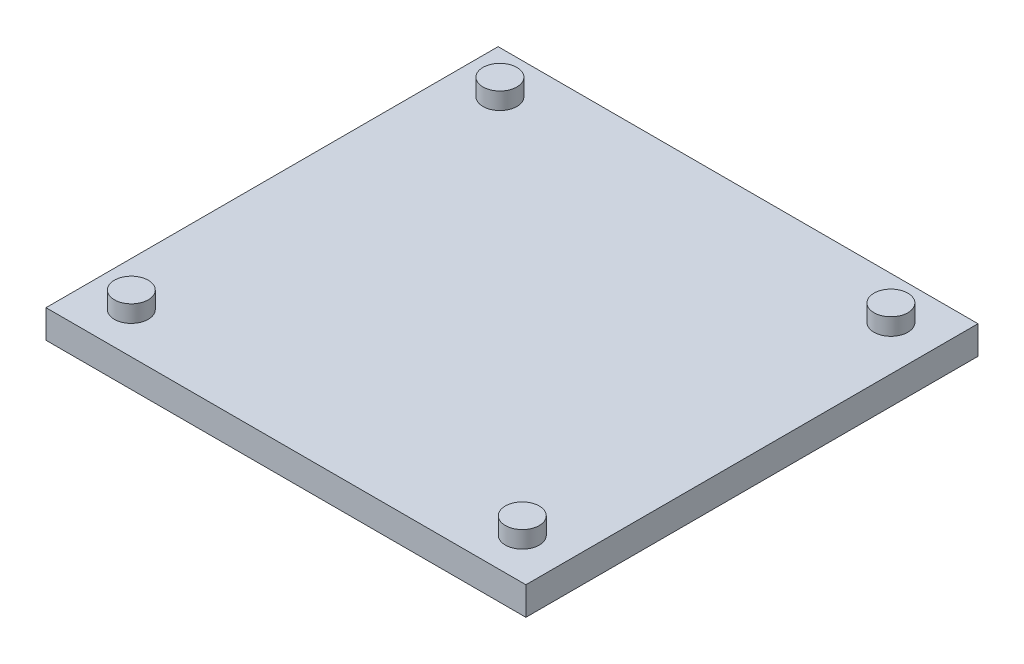
SolidWorks part; units mm, degrees
ref_plane "前视基准面" through (0, 0, 0) normal (0, 0, 1) x (1, 0, 0)
ref_plane "上视基准面" through (0, 0, 0) normal (0, 1, 0) x (1, 0, 0)
ref_plane "右视基准面" through (0, 0, 0) normal (1, 0, 0) x (0, 0, -1)
other "Configuration Table"
sketch "草图4" plane through (0, 0, 0) normal (0, 1, 0) x (1, 0, 0)
  line L0 (-44.4257, -18.1171) -> (-44.4257, -98.1171)
  line L1 (-44.4257, -18.1171) -> (40.4907, -18.1171)
  line L2 (-44.4257, -98.1171) -> (40.4907, -98.1171)
  line L3 (40.4907, -18.1171) -> (40.4907, -98.1171)
  circle A0 centre (-36.5851, -25.6363) radius 3
  circle A1 centre (32.6016, -25.6363) radius 3
  circle A2 centre (-36.5851, -90.862) radius 3
  circle A3 centre (32.6016, -90.862) radius 3
extrude "凸台-拉伸1" add sketch "草图4" along normal blind 5
sketch "草图5" plane through (0, 5, 0) normal (0, 1, 0) x (1, 0, 0)
  circle A0 centre (-36.5851, -25.6363) radius 3
  circle A1 centre (32.6016, -25.6363) radius 3
  circle A2 centre (-36.5851, -90.862) radius 3
  circle A3 centre (32.6016, -90.862) radius 3
extrude "凸台-拉伸2" add sketch "草图5" along normal blind 3 and the other way blind 5
